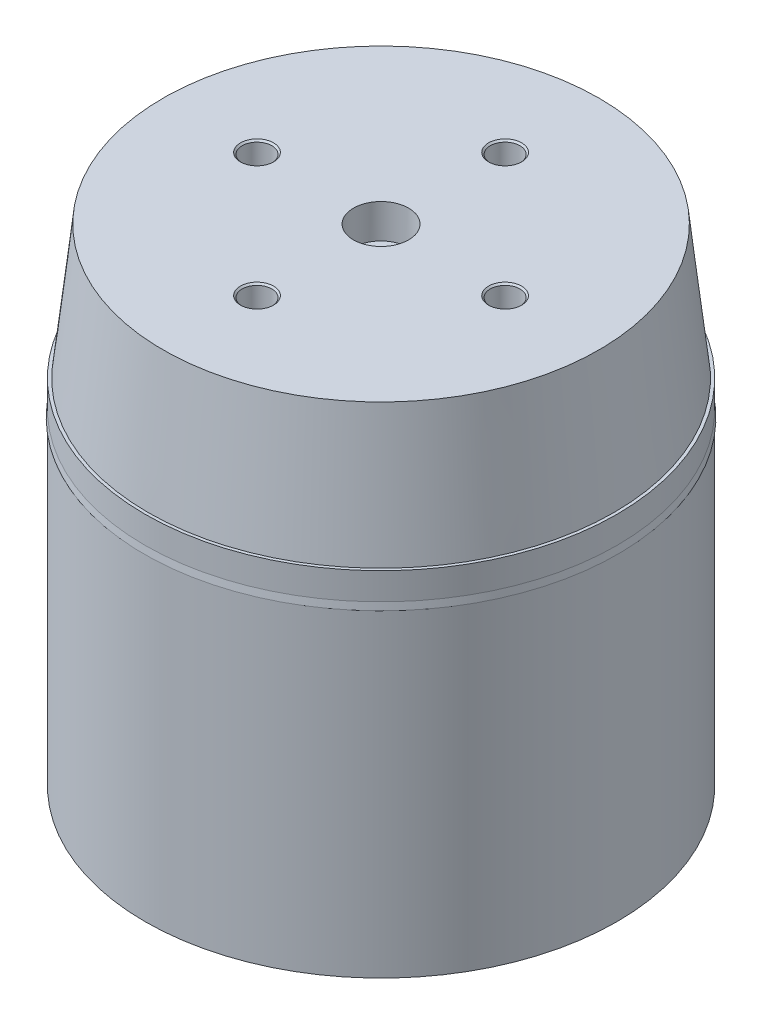
SolidWorks part; units mm, degrees
ref_plane "前视基准面" through (0, 0, 0) normal (0, 0, 1) x (1, 0, 0)
ref_plane "上视基准面" through (0, 0, 0) normal (0, 1, 0) x (1, 0, 0)
ref_plane "右视基准面" through (0, 0, 0) normal (1, 0, 0) x (0, 0, -1)
sketch "草图1" plane through (0, 0, 0) normal (0, 1, 0) x (1, 0, 0)
  circle A0 centre (0, 0) radius 21.4
  circle A1 centre (0, 0) radius 18
  dimension "D1" = 42.8
  dimension "D2" = 36
extrude "凸台-拉伸1" add sketch "草图1" along normal blind 32
sketch "草图5" plane through (0, 0, 0) normal (1, 0, 0) x (0, 0, -1)
  line L0 (0, 0) -> (0, 41) construction
  dimension "D1" = 41
sketch "草图11" plane through (0, 0, 0) normal (1, 0, 0) x (0, 0, -1)
  line L0 (-17, 41) -> (-18.007, 32)
  line L1 (21.4, 32) -> (-21.4, 32) construction
  line L2 (0, 0) -> (0, 41) construction
  line L3 (0, 41) -> (-17, 41)
  line L5 (0, 32) -> (-18.007, 32)
  dimension "D1" = 9
  dimension "D4" = 17
revolve "旋转-薄壁4" add sketch "草图11" angle 360 about L0
sketch "草图13" plane through (0, 44.1, 0) normal (0, 1, 0) x (1, 0, 0)
  circle A0 centre (0, 0) radius 2.5
  dimension "D1" = 5
extrude "切除-拉伸1" cut sketch "草图13" against normal through all contours A0
sketch "草图16" plane through (0, 44.1, 0) normal (0, 1, 0) x (1, 0, 0)
  circle A0 centre (0, 0) radius 11.25 construction
  circle A1 centre (0, 11.25) radius 1.5
  circle A2 centre (11.25, 0) radius 1.5
  circle A3 centre (0, -11.25) radius 1.5
  circle A4 centre (-11.25, 0) radius 1.5
  point P14 (0, 0)
  dimension "D1" = 3
  dimension "D2" = 22.5
  dimension "D3" = 4
hole_wizard "打孔尺寸(%根据)内六角花形半沉头螺钉的类型1" positions "3D草图1" profile "草图17" countersink size "M6" standard "GB" end condition through all
sketch3d "3D草图1"
  point P0 (0, 44.1, -11.25)
  point P3 (11.25, 44.1, 0)
  point P6 (0, 44.1, 11.25)
  point P9 (-11.25, 44.1, 0)
sketch "草图17" plane through (0, 44.1, -11.25) normal (1, 0, 0) x (0, 0, 1)
  line L0 (0, 0) -> (0, 44.1)
  line L1 (0, 44.1) -> (1.35, 44.1)
  line L2 (1.35, 44.1) -> (1.35, 0.15)
  line L3 (1.35, 0.15) -> (1.5, 0)
  line L5 (1.5, 0) -> (0, 0)
  line L6 (-1.35, 0.15) -> (-1.5, 0) construction
  line L11 (0, -6.35) -> (0, 107.95) construction
  dimension "通孔孔直径" = 2.7
  dimension "通孔孔深度" = 44.1
  dimension "近端锥形沉头孔直径" = 3
  dimension "近端锥形沉头孔角度" = 90
